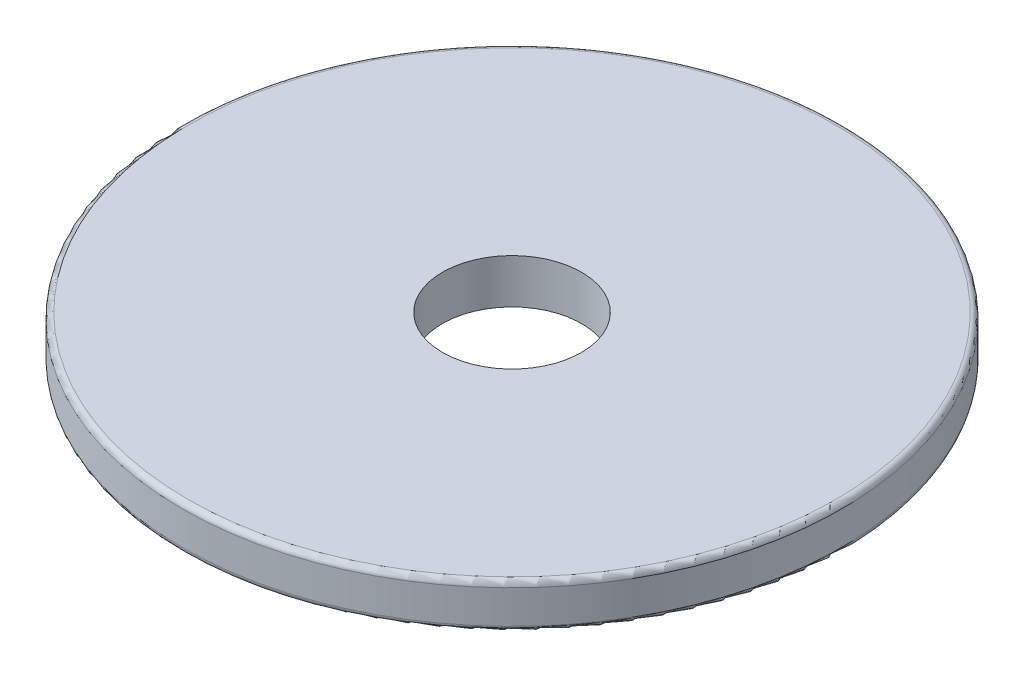
SolidWorks part; units mm, degrees
material "AISI 4340 Aço recozido"
ref_plane "Plano frontal" through (0, 0, 0) normal (0, 0, 1) x (1, 0, 0)
ref_plane "Plano superior" through (0, 0, 0) normal (0, 1, 0) x (1, 0, 0)
ref_plane "Plano direito" through (0, 0, 0) normal (1, 0, 0) x (0, 0, -1)
sketch "Esboço1" plane through (0, 0, 0) normal (0, 1, 0) x (1, 0, 0)
  circle A0 centre (0, 0) radius 11.85
  circle A1 centre (0, 0) radius 2.5
  dimension "D1" = 23.7
  dimension "D2" = 5
extrude "Ressalto-extrusão1" add sketch "Esboço1" along normal mid plane 1.6
fillet "Filete1" radius 0.2 2 edges at (0, -0.8, 11.85) (0, 0.8, 11.85)
